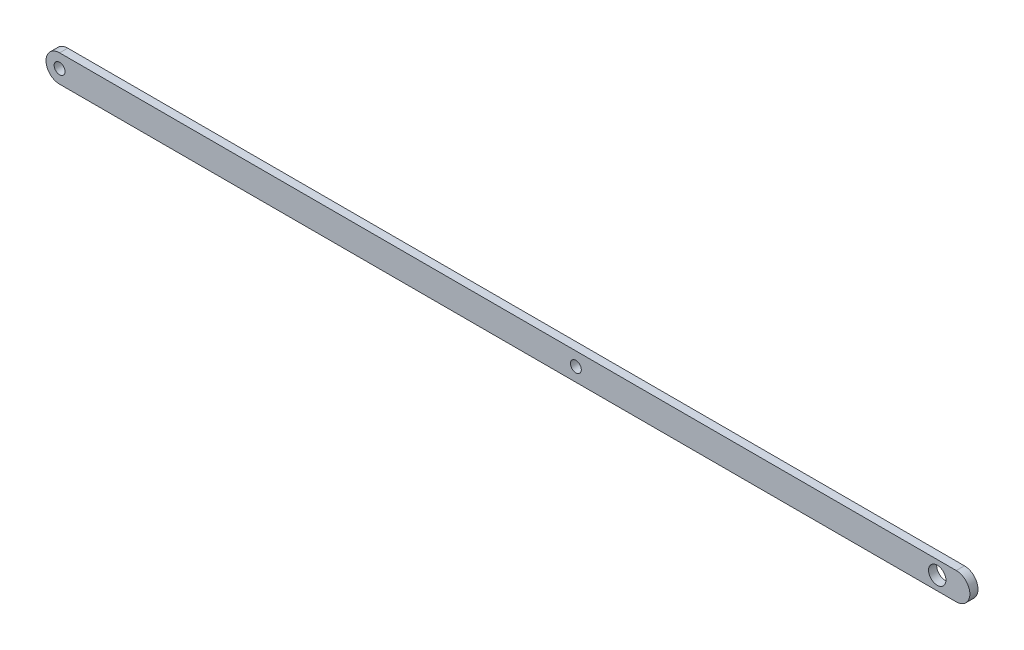
SolidWorks part; units mm, degrees
material "E fiberglass"
ref_plane "Front Plane" through (0, 0, 0) normal (0, 0, 1) x (1, 0, 0)
ref_plane "Top Plane" through (0, 0, 0) normal (0, 1, 0) x (1, 0, 0)
ref_plane "Right Plane" through (0, 0, 0) normal (1, 0, 0) x (0, 0, -1)
sketch "Sketch1" plane through (0, 0, 0) normal (0, 0, 1) x (1, 0, 0)
  line L0 (0, 0) -> (330, 0) construction
  line L1 (0, 5) -> (330, 5)
  line L2 (0, -5) -> (330, -5)
  arc A0 (0, 5) -> (0, -5) centre (0, 0) ccw
  arc A1 (330, -5) -> (330, 5) centre (330, 0) ccw
  point P3 (165, 0)
  dimension "D1" = 330
  dimension "D2" = 10
extrude "Boss-Extrude1" add sketch "Sketch1" along normal blind 3
sketch "Sketch2" plane through (0, 0, 3) normal (0, 0, 1) x (1, 0, 0)
  circle A0 centre (323, 0) radius 3.2
  arc A1 (330, -5) -> (330, 5) centre (330, 0) ccw construction
  point P5 (335, 0)
  dimension "D1" = 6.4
  dimension "D2" = 12
extrude "Cut-Extrude1" cut sketch "Sketch2" against normal up to surface (3 mm away) up to face at (165, 0, 0)
sketch "Sketch5" plane through (0, 0, 3) normal (0, 0, 1) x (1, 0, 0)
  circle A0 centre (190, 0) radius 2
  arc A1 (330, -5) -> (330, 5) centre (330, 0) ccw construction
  point P7 (335, 0)
  dimension "D1" = 4
  dimension "D3" = 145
extrude "Cut-Extrude2" cut sketch "Sketch5" against normal up to surface (3 mm away) up to face at (326.2, 0, 0)
sketch "Sketch6" plane through (0, 0, 3) normal (0, 0, 1) x (1, 0, 0)
  circle A0 centre (0, 0) radius 2.5
  dimension "D1" = 5
split line "Split Line1" [suppressed]
sketch "Sketch7" [suppressed] plane through (0, 0, 3) normal (0, 0, 1) x (1, 0, 0)
  circle A0 centre (0, 0) radius 2
  dimension "D1" = 4
extrude "Cut-Extrude3" [suppressed] cut sketch "Sketch7" against normal up to surface (3 mm away)
ref_plane "Plane1" through (0.8551, 0.1508, 0) normal (0.9848, 0.1736, 0) x (0, 0, -1)
sketch "Sketch8" [suppressed] plane through (0.8551, 0.1508, 0) normal (0.9848, 0.1736, 0) x (0, 0, -1)
  line L0 (0, -4.924) -> (0, 5) construction
  line L1 (0, -3.5689) -> (-3, -3.5689)
  line L2 (0, -3.5689) -> (0, 1.7352)
  line L3 (0, 1.7352) -> (-3, 1.7352)
  line L4 (-3, -3.5689) -> (-3, 1.7352)
  line L5 (-3, -4.924) -> (-3, -62.2279) construction
split line "Split Line2" [suppressed]
sketch "Sketch10" plane through (0, 0, 3) normal (0, 0, 1) x (1, 0, 0)
  circle A0 centre (0, 0) radius 2
  dimension "D1" = 4
extrude "Cut-Extrude4" cut sketch "Sketch10" against normal up to surface (3 mm away) up to face at (192, 0, 0)
equation "\"BarWidth\"=10"
